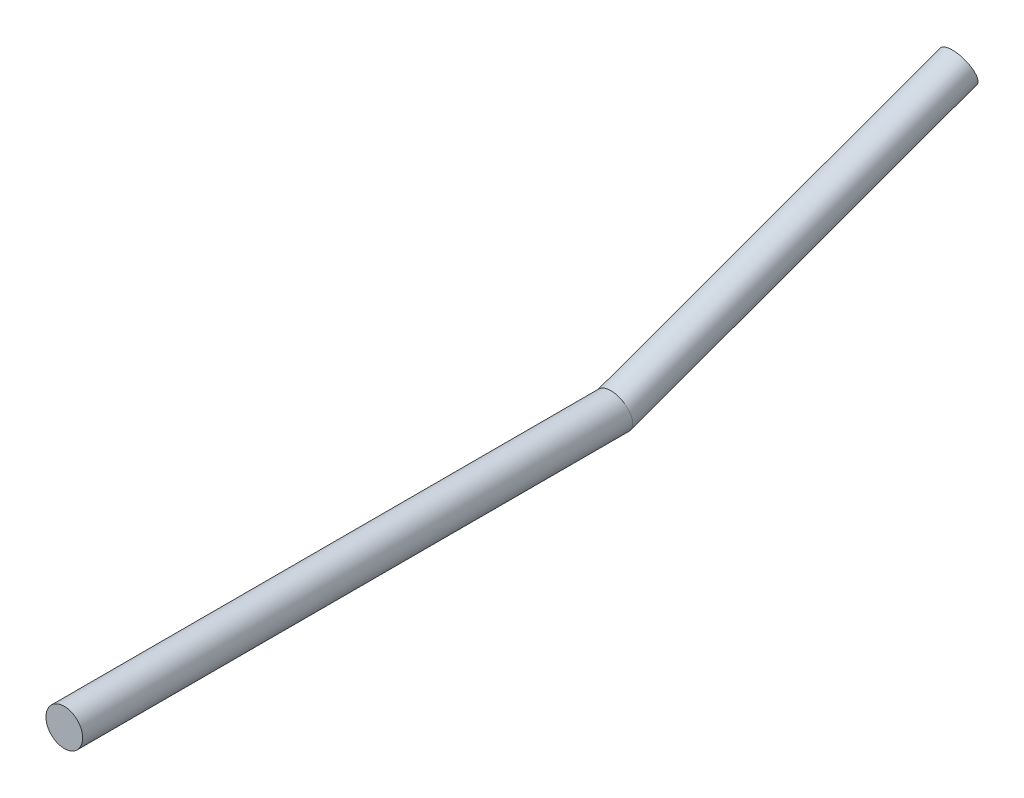
SolidWorks part; units mm, degrees
ref_plane "Front Plane" through (0, 0, 0) normal (0, 0, 1) x (1, 0, 0)
ref_plane "Top Plane" through (0, 0, 0) normal (0, 1, 0) x (1, 0, 0)
ref_plane "Right Plane" through (0, 0, 0) normal (1, 0, 0) x (0, 0, -1)
sketch "Sketch1" plane through (0, 0, 0) normal (1, 0, 0) x (0, 0, -1)
  line L0 (-37.49, 0) -> (0, 0)
  line L1 (0, 0) -> (23.4923, 8.5505)
  dimension "D1" = 200
  dimension "D2" = 25
  dimension "D3" = 37.49
sketch "Sketch2" plane through (0, 0, 0) normal (0, 0, 1) x (1, 0, 0)
  circle A0 centre (0, 0) radius 1.25
  point P4 (0, 0)
  dimension "D1" = 2.5
sweep "Sweep1" add profiles "Sketch2" path "Sketch1"
ref_plane "Plane1" through (0, 0, 0.49) normal (0, 0, 1) x (1, 0, 0)
sketch "Sketch3" plane through (0, 0, 0.49) normal (0, 0, 1) x (1, 0, 0)
  circle A0 centre (0, 0) radius 1.75
  circle A1 centre (0, 0) radius 1.25
  dimension "D1" = 3.5
  dimension "D2" = 2.5
extrude "Boss-Extrude1" [suppressed] add sketch "Sketch3" against normal blind 3
ref_plane "Plane2" [suppressed] through (0, 0, 34.5) normal (0, 0, 1) x (1, 0, 0)
sketch "Sketch5" [suppressed] plane through (0, 0, 34.5) normal (0, 0, 1) x (1, 0, 0)
  line L1 (-3.865, 3.5524) -> (3.3798, 3.5524)
  line L2 (-3.865, 3.5524) -> (-3.865, -2.5119)
  line L3 (-3.865, -2.5119) -> (3.3798, -2.5119)
  line L4 (3.3798, 3.5524) -> (3.3798, -2.5119)
extrude "Cut-Extrude1" [suppressed] cut sketch "Sketch5" along normal through all
sketch "Sketch6" [suppressed] plane through (0, 0, 34.5) normal (0, 0, 1) x (1, 0, 0)
  circle A0 centre (0, 0) radius 0.925
  dimension "D1" = 1.85
extrude "Cut-Extrude2" [suppressed] cut sketch "Sketch6" against normal blind 33
sketch "Sketch7" plane through (0, 8.5505, -23.4923) normal (0, 0.342, -0.9397) x (-1, 0, 0)
  circle A0 centre (0, 0) radius 0.925
  dimension "D1" = 1.85
extrude "Cut-Extrude3" [suppressed] cut sketch "Sketch7" against normal blind 22
